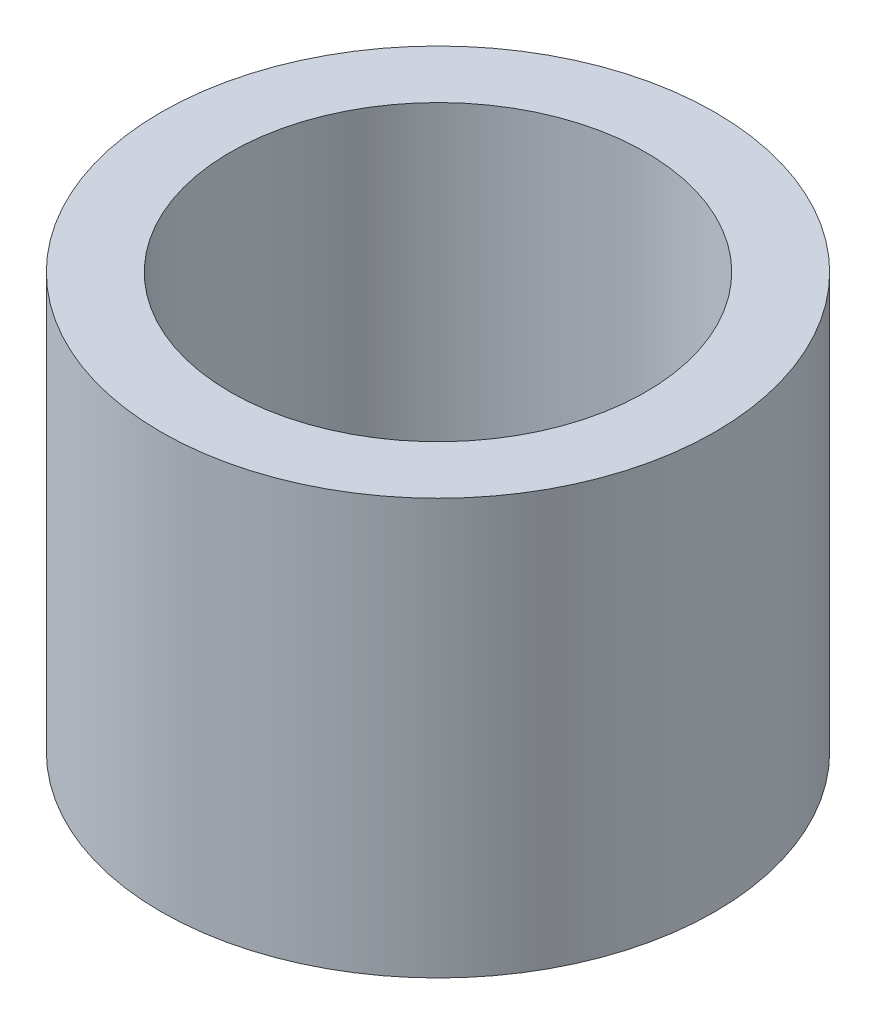
SolidWorks part; units mm, degrees
ref_plane "Front" through (0, 0, 0) normal (0, 0, 1) x (1, 0, 0)
ref_plane "Top" through (0, 0, 0) normal (0, 1, 0) x (1, 0, 0)
ref_plane "Right" through (0, 0, 0) normal (1, 0, 0) x (0, 0, -1)
sketch "Sketch1" plane through (0, 0, 0) normal (0, 1, 0) x (1, 0, 0)
  circle A0 centre (0, 0) radius 3
  circle A1 centre (0, 0) radius 4
extrude "Boss-Extrude1" add sketch "Sketch1" along normal blind 6
